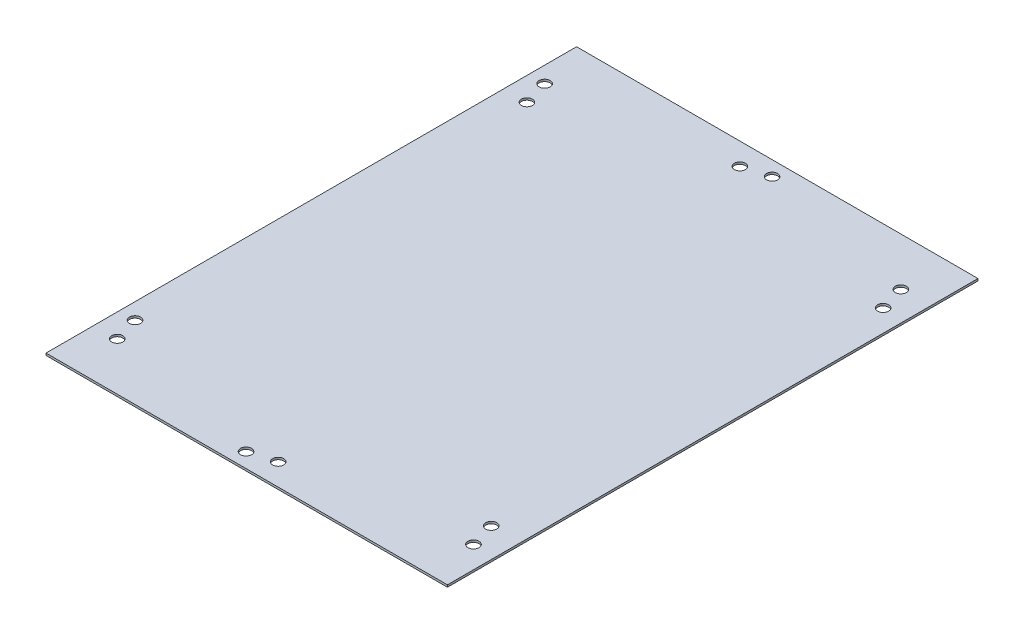
SolidWorks part; units mm, degrees
material "Alumina"
ref_plane "Front Plane" through (0, 0, 0) normal (0, 0, 1) x (1, 0, 0)
ref_plane "Top Plane" through (0, 0, 0) normal (0, 1, 0) x (1, 0, 0)
ref_plane "Right Plane" through (0, 0, 0) normal (1, 0, 0) x (0, 0, -1)
sketch "Sketch3" plane through (0, 0, 0) normal (0, 1, 0) x (1, 0, 0)
  line L1 (-122.5, 161.9) -> (122.5, 161.9)
  line L2 (-122.5, 161.9) -> (-122.5, -161.9)
  line L3 (-122.5, -161.9) -> (122.5, -161.9)
  line L4 (122.5, 161.9) -> (122.5, -161.9)
  line L5 (-122.5, 161.9) -> (122.5, -161.9) construction
  line L6 (-122.5, -161.9) -> (122.5, 161.9) construction
  point P0 (0, 0)
  dimension "D1" = 323.8
  dimension "D2" = 245
extrude "Boss-Extrude1" add sketch "Sketch3" along normal blind 1.2954
sketch "Sketch4" plane through (0, 1.2954, 0) normal (0, 1, 0) x (1, 0, 0)
  circle A0 centre (109.1046, -132.62) radius 3.3782
  circle A1 centre (104.7046, -117.38) radius 3.3782
  circle A2 centre (5.8246, -148.5) radius 3.3782
  circle A3 centre (-9.4154, -152.9) radius 3.3782
  circle A4 centre (109.1046, 117.38) radius 3.3782
  circle A6 centre (104.7046, 132.62) radius 3.3782
  circle A7 centre (5.8246, 152.9) radius 3.3782
  circle A8 centre (-9.4154, 148.5) radius 3.3782
  circle A9 centre (-108.2954, 117.38) radius 3.3782
  circle A10 centre (-112.6954, 132.62) radius 3.3782
  circle A11 centre (-108.2954, -132.62) radius 3.3782
  circle A12 centre (-112.6954, -117.38) radius 3.3782
extrude "Cut-Extrude1" cut sketch "Sketch4" against normal up to next
